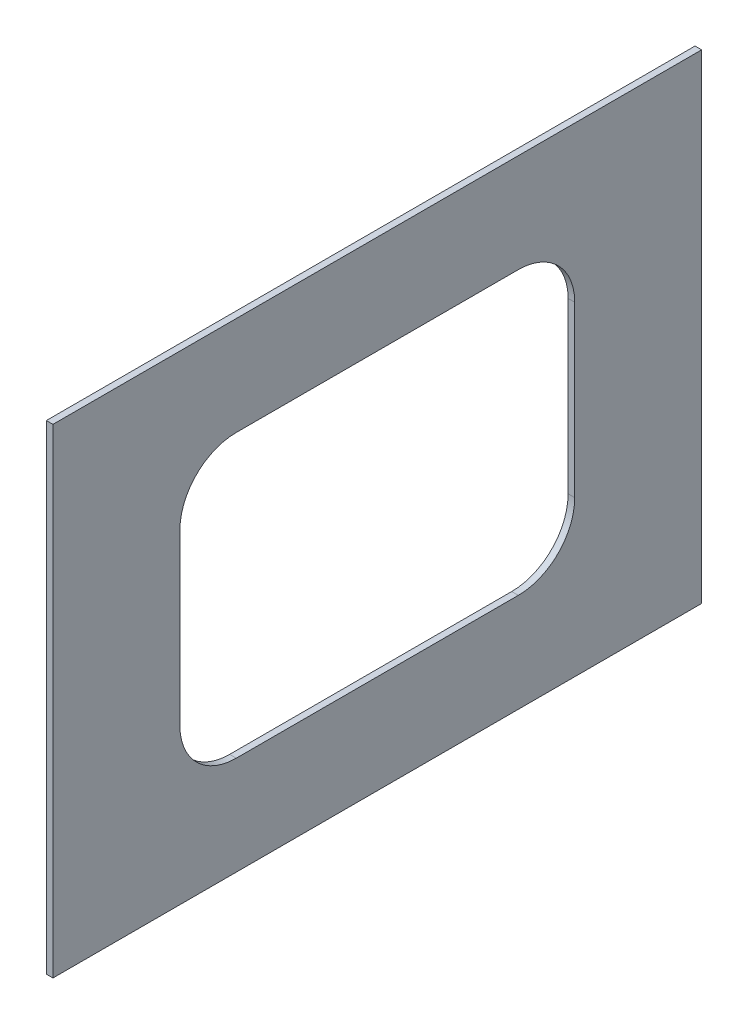
SolidWorks part; units mm, degrees
material "Pine"
ref_plane "Front Plane" through (0, 0, 0) normal (0, 0, 1) x (1, 0, 0)
ref_plane "Top Plane" through (0, 0, 0) normal (0, 1, 0) x (1, 0, 0)
ref_plane "Right Plane" through (0, 0, 0) normal (1, 0, 0) x (0, 0, -1)
sketch "Sketch1" plane through (0, 0, 0) normal (1, 0, 0) x (0, 0, -1)
  line L0 (228.6, 279.4) -> (0, 279.4) construction
  line L1 (0, 0) -> (1168.4, 0)
  line L2 (0, 0) -> (0, 863.6)
  line L3 (0, 863.6) -> (1168.4, 863.6)
  line L4 (1168.4, 0) -> (1168.4, 863.6)
  line L5 (330.2, 685.8) -> (838.2, 685.8)
  line L6 (228.6, 584.2) -> (228.6, 279.4)
  line L7 (330.2, 177.8) -> (838.2, 177.8)
  line L8 (939.8, 584.2) -> (939.8, 279.4)
  line L9 (939.8, 279.4) -> (1168.4, 279.4) construction
  arc A4 (228.6, 279.4) -> (330.2, 177.8) centre (330.2, 279.4) ccw
  arc A5 (838.2, 177.8) -> (939.8, 279.4) centre (838.2, 279.4) ccw
  arc A6 (838.2, 685.8) -> (939.8, 584.2) centre (838.2, 584.2) cw
  arc A7 (330.2, 685.8) -> (228.6, 584.2) centre (330.2, 584.2) ccw
  point P24 (228.6, 177.8)
  point P27 (939.8, 177.8)
  point P30 (939.8, 685.8)
  dimension "D12" = 101.6
  dimension "D1" = 863.6
  dimension "D2" = 1168.4
  dimension "D3" = 177.8
  dimension "D4" = 711.2
  dimension "D5" = 508
extrude "Boss-Extrude1" add sketch "Sketch1" along normal blind 11.9062
